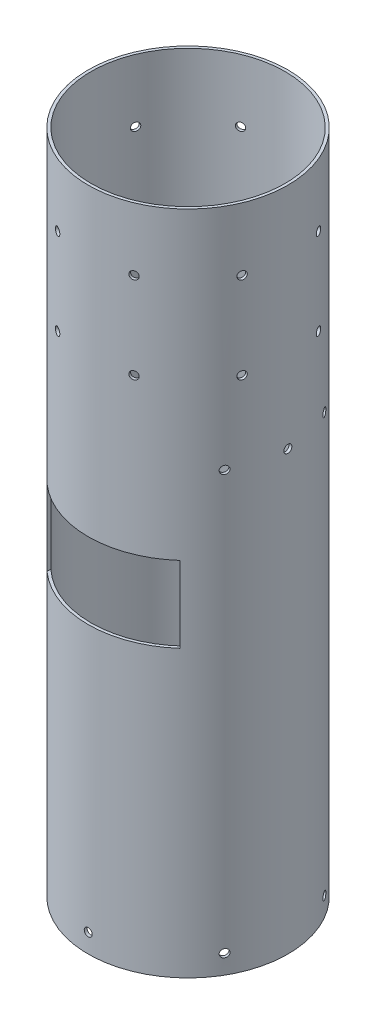
SolidWorks part; units mm, degrees
ref_plane "Спереди" through (0, 0, 0) normal (0, 0, 1) x (1, 0, 0)
ref_plane "Сверху" through (0, 0, 0) normal (0, 1, 0) x (1, 0, 0)
ref_plane "Справа" through (0, 0, 0) normal (1, 0, 0) x (0, 0, -1)
sketch "Эскиз1" plane through (0, 0, 0) normal (0, 0, 1) x (1, 0, 0)
  line L0 (0, 0) -> (0, 131.5742) construction
  line L1 (52.5, 350) -> (52.5, 0)
  line L2 (52.5, 0) -> (51, 0)
  line L3 (51, 0) -> (51, 350)
  line L4 (51, 350) -> (52.5, 350)
  dimension "D1" = 1.5
  dimension "D2" = 102
  dimension "D3" = 350
revolve "Повернуть1" add sketch "Эскиз1" angle 360 about L0
sketch "Эскиз2" plane through (0, 0, 0) normal (0, 0, 1) x (1, 0, 0)
  circle A0 centre (0, 10) radius 2.1
  dimension "D1" = 4.2
  dimension "D2" = 10
extrude "Вырез-Вытянуть2" cut sketch "Эскиз2" against normal blind 88 contours A0
pattern_circular "Круговой массив2" count 6 over 360 about axis through (0, 0, 0) along (0, -1, 0) of "Вырез-Вытянуть2"
sketch "Эскиз3" plane through (0, 0, 0) normal (1, 0, 0) x (0, 0, -1)
  line L0 (51, 350) -> (-51, 350) construction
  circle A0 centre (0, 319) radius 2.1
  dimension "D1" = 4.2
  dimension "D2" = 31
sketch "Эскиз5" plane through (0, 0, 0) normal (0, 1, 0) x (1, 0, 0)
  line L0 (0, 0) -> (0, -51) construction
  line L1 (0, 0) -> (36.0624, -36.0624) construction
  line L2 (0, 0) -> (51, 0) construction
  line L4 (0, 0) -> (19.5169, -47.1179) construction
  line L5 (0, -51) -> (19.5169, -47.1179) construction
  line L6 (0, -51) -> (36.0624, -36.0624) construction
  circle A0 centre (0, 0) radius 51 construction
  dimension "D1" = 45
  dimension "D2" = 22.5
ref_plane "Плоскость2" through (9.7584, 0, 49.0589) normal (0.1951, 0, 0.9808) x (0.9808, 0, -0.1951)
sketch "Эскиз7" plane through (9.7584, 0, 49.0589) normal (0.1951, 0, 0.9808) x (0.9808, 0, -0.1951)
  line L0 (0, 350) -> (0, 0) construction
  line L1 (51, 350) -> (-51, 350) construction
  circle A0 centre (0, 314.5) radius 2.2
  circle A1 centre (0, 269) radius 2.1
  dimension "D1" = 4.4
  dimension "D2" = 35.5
  dimension "D3" = 4.2
  dimension "D4" = 45.5
ref_plane "Плоскость3" through (18.0312, 0, 43.5312) normal (0.3827, 0, 0.9239) x (0.9239, 0, -0.3827)
sketch "Эскиз8" plane through (18.0312, 0, 43.5312) normal (0.3827, 0, 0.9239) x (0.9239, 0, -0.3827)
  line L0 (0, 350) -> (0, 0) construction
  line L1 (51, 350) -> (-51, 350) construction
  circle A0 centre (0, 317) radius 2.1
  circle A1 centre (0, 271.5) radius 2.1
  dimension "D1" = 4.2
  dimension "D2" = 33
  dimension "D3" = 4.2
  dimension "D4" = 45.5
extrude "Вырез-Вытянуть3" cut sketch "Эскиз8" along normal blind 32
pattern_circular "Круговой массив3" count 8 over 360 about axis through (0, 0, 0) along (0, -1, 0) of "Вырез-Вытянуть3"
sketch "Эскиз9" plane through (0, 0, 0) normal (1, 0, 0) x (0, 0, -1)
  line L0 (0, 350) -> (0, 230) construction
  line L1 (0, 350) -> (0, 0) construction
  line L2 (51, 350) -> (-51, 350) construction
  line L3 (51, 350) -> (-51, 350)
  circle A0 centre (0, 230) radius 2.1
  dimension "D2" = 4.2
  dimension "D1" = 120
extrude "Вырез-Вытянуть4" cut sketch "Эскиз9" along normal blind 171 contours A0
pattern_circular "Круговой массив4" count 2 every 30 about axis through (0, 0, 0) along (0, -1, 0) of "Вырез-Вытянуть4"
sketch "Эскиз10" plane through (0, 0, 0) normal (0, 0, 1) x (1, 0, 0)
  line L0 (0, -1000) -> (0, 49000) construction
  line L2 (35, 190) -> (-35, 190)
  line L3 (35, 190) -> (35, 150)
  line L4 (35, 150) -> (-35, 150)
  line L5 (-35, 190) -> (-35, 150)
  line L6 (35, 190) -> (-35, 150) construction
  line L7 (35, 150) -> (-35, 190) construction
  point P1 (0, 170)
  point P8 (35, 170)
  dimension "D1" = 40
  dimension "D2" = 150
  dimension "D3" = 70
extrude "Вырез-Вытянуть5" cut sketch "Эскиз10" along normal through all
